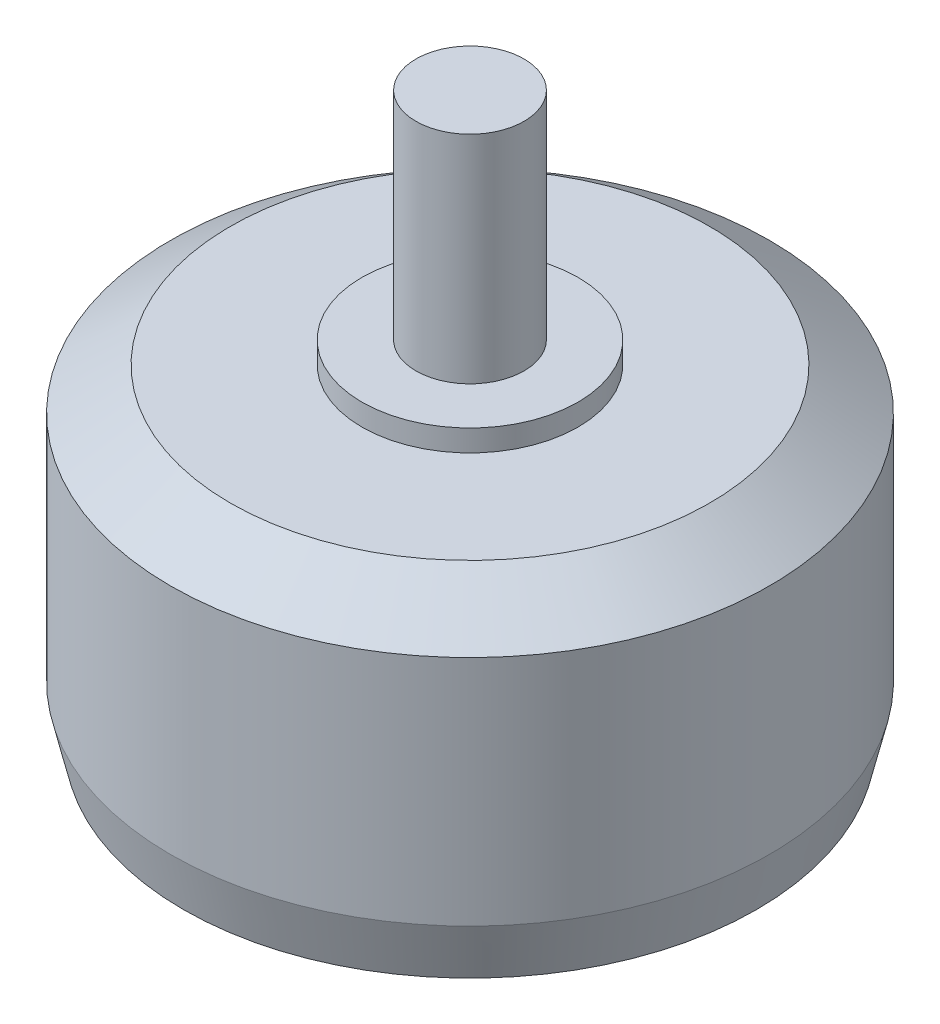
SolidWorks part; units mm, degrees
ref_plane "Front Plane" through (0, 0, 0) normal (0, 0, 1) x (1, 0, 0)
ref_plane "Top Plane" through (0, 0, 0) normal (0, 1, 0) x (1, 0, 0)
ref_plane "Right Plane" through (0, 0, 0) normal (1, 0, 0) x (0, 0, -1)
sketch "Sketch1" plane through (0, 0, 0) normal (1, 0, 0) x (0, 0, -1)
  line L0 (0, 0) -> (-13.2573, 0)
  line L1 (-13.2573, 0) -> (-13.85, 2.5035)
  line L2 (-13.85, 2.5035) -> (-13.85, 13.2611)
  line L3 (-13.85, 13.2611) -> (-11.0869, 15.2)
  line L4 (-11.0869, 15.2) -> (-5, 15.2)
  line L5 (-5, 15.2) -> (-5, 16.2)
  line L6 (-5, 16.2) -> (-2.5, 16.2)
  line L7 (-2.5, 16.2) -> (-2.5, 26.2)
  line L8 (-2.5, 26.2) -> (0, 26.2)
  line L9 (0, 26.2) -> (0, 0)
  point P3 (-13.3686, 0)
  point P12 (-13.3686, 3.2574)
  point P13 (-3.4023, 2.8127)
  point P14 (-11.0869, 15.2)
  point P15 (-13.85, 13.2611)
  point P16 (-13.85, 2.5035)
  point P17 (-13.2573, 0)
  dimension "D1" = 2.5
  dimension "D2" = 11
  dimension "D3" = 13.85
  dimension "D4" = 15.2
  dimension "D5" = 2.5
  dimension "D6" = 1
revolve "Revolve1" add sketch "Sketch1" angle 360 about L9
sketch "Sketch2" plane through (0, 0, 0) normal (0, -1, 0) x (1, 0, 0)
  line L0 (-8, 0) -> (8, 0) construction
  line L1 (0, 6) -> (0, -6) construction
  circle A0 centre (0, 6) radius 1
  circle A1 centre (8, 0) radius 1
  circle A2 centre (0, -6) radius 1
  circle A3 centre (-8, 0) radius 1
  dimension "D1" = 16
  dimension "D3" = 2
  dimension "D2" = 12
extrude "Cut-Extrude1" cut sketch "Sketch2" against normal blind 10.16
